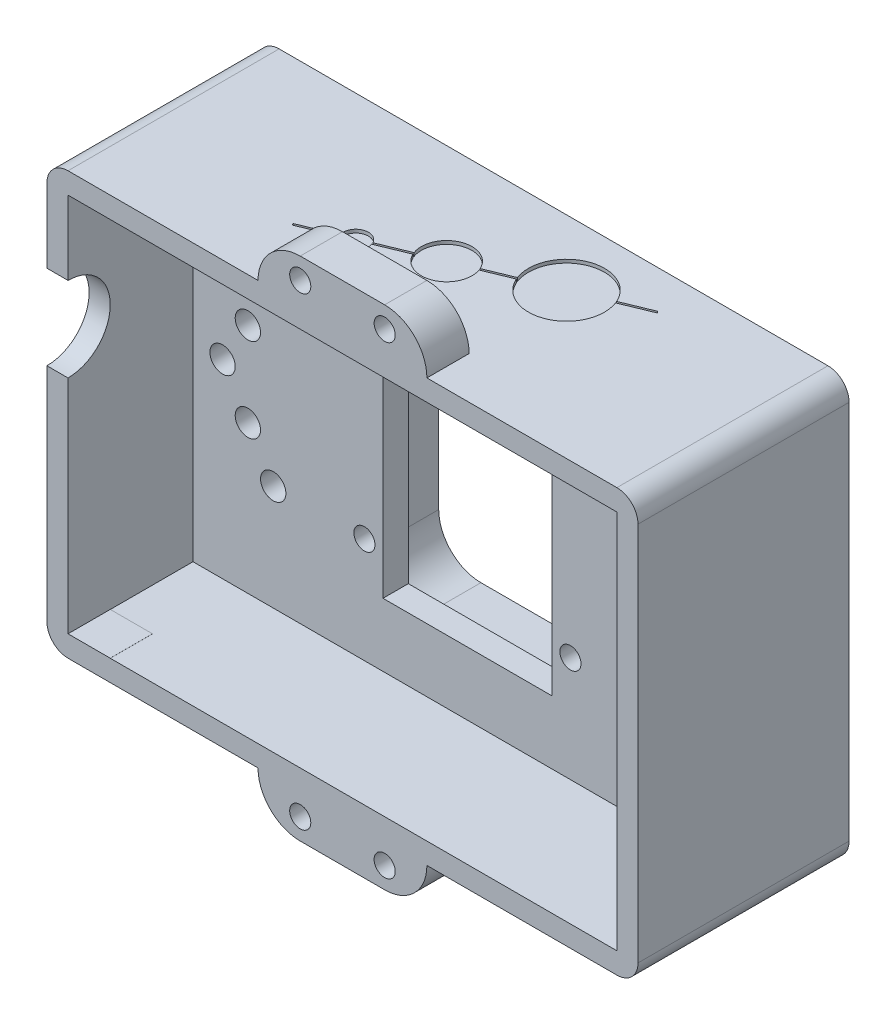
SolidWorks part; units mm, degrees
ref_plane "Front Plane" through (0, 0, 0) normal (0, 0, 1) x (1, 0, 0)
ref_plane "Top Plane" through (0, 0, 0) normal (0, 1, 0) x (1, 0, 0)
ref_plane "Right Plane" through (0, 0, 0) normal (1, 0, 0) x (0, 0, -1)
sketch "Sketch1" plane through (0, 0, 0) normal (0, 0, 1) x (1, 0, 0)
  line L1 (0, 0) -> (76.2, 0)
  line L2 (0, 0) -> (0, -63.5)
  line L3 (0, -63.5) -> (76.2, -63.5)
  line L4 (76.2, 0) -> (76.2, -63.5)
  dimension "D1" = 76.2
  dimension "D2" = 63.5
extrude "Boss-Extrude1" add sketch "Sketch1" along normal blind 31.75
sketch "Sketch2" plane through (0, 0, 31.75) normal (0, 0, 1) x (1, 0, 0)
  line L0 (0, 0) -> (0, -63.5) construction
  line L1 (3.175, -3.175) -> (73.025, -3.175)
  line L2 (3.175, -3.175) -> (3.175, -60.325)
  line L3 (3.175, -60.325) -> (73.025, -60.325)
  line L4 (73.025, -3.175) -> (73.025, -60.325)
  line L5 (76.2, 0) -> (0, 0) construction
  line L6 (76.2, -63.5) -> (76.2, 0) construction
  line L7 (0, -63.5) -> (76.2, -63.5) construction
  dimension "D1" = 3.175
  dimension "D2" = 3.175
  dimension "D3" = 3.175
  dimension "D4" = 3.175
extrude "Cut-Extrude1" cut sketch "Sketch2" against normal blind 28.575
sketch "Sketch3" plane through (0, 0, 0) normal (0, 0, -1) x (-1, 0, 0)
  line L0 (-76.2, 0) -> (0, 0) construction
  line L1 (-47.625, -19.05) -> (-28.575, -19.05)
  line L2 (-47.625, -19.05) -> (-47.625, -44.45)
  line L3 (-47.625, -44.45) -> (-28.575, -44.45)
  line L4 (-28.575, -19.05) -> (-28.575, -44.45)
  line L5 (-76.2, -63.5) -> (-76.2, 0) construction
  point P4 (-38.1, -19.05)
  dimension "D1" = 19.05
  dimension "D2" = 25.4
  dimension "D3" = 19.05
  dimension "D4" = 28.575
extrude "Cut-Extrude2" cut sketch "Sketch3" against normal blind 28.575
sketch "Sketch4" plane through (0, 0, 0) normal (0, 0, -1) x (-1, 0, 0)
  line L0 (-47.625, -19.05) -> (-47.625, -44.45) construction
  line L1 (-28.575, -44.45) -> (-28.575, -19.05) construction
  line L3 (-76.2, 0) -> (0, 0) construction
  line L4 (0, -63.5) -> (-76.2, -63.5) construction
  line L5 (-47.625, -19.05) -> (-47.625, -12.7)
  line L6 (-47.625, -12.7) -> (-28.575, -12.7)
  line L7 (-28.575, -12.7) -> (-28.575, -19.05)
  line L8 (-28.575, -19.05) -> (-47.625, -19.05)
  circle A0 centre (-52.0383, -19.05) radius 1.5875
  circle A1 centre (-24.257, -19.05) radius 1.5875
  circle A2 centre (-52.0382, -44.45) radius 1.5875
  circle A3 centre (-24.257, -44.45) radius 1.5875
  dimension "D1" = 3.175
  dimension "D2" = 27.7812
  dimension "D3" = 4.4132
  dimension "D4" = 4.4132
  dimension "D5" = 27.7812
  dimension "D6" = 4.318
  dimension "D7" = 4.318
  dimension "D8" = 19.05
  dimension "D9" = 19.05
  dimension "D10" = 6.35
extrude "Cut-Extrude3" cut sketch "Sketch4" against normal blind 28.575
sketch "Sketch5" plane through (0, 0, 0) normal (0, 0, -1) x (-1, 0, 0)
  line L0 (-47.625, -44.45) -> (-47.625, -50.8)
  line L1 (-47.625, -50.8) -> (-28.575, -50.8)
  line L2 (-28.575, -50.8) -> (-28.575, -44.45)
  line L3 (-47.625, -44.45) -> (-28.575, -44.45)
  dimension "D1" = 6.35
extrude "Cut-Extrude4" cut sketch "Sketch5" against normal blind 28.575
sketch "Sketch7" plane through (0, 0, 0) normal (0, 1, 0) x (1, 0, 0)
  line L0 (76.2, -31.75) -> (0, -31.75) construction
  line L1 (25.4, -31.75) -> (50.8, -31.75)
  line L2 (25.4, -31.75) -> (25.4, -25.4)
  line L3 (25.4, -25.4) -> (50.8, -25.4)
  line L4 (50.8, -31.75) -> (50.8, -25.4)
  line L5 (0, -31.75) -> (0, 0) construction
  dimension "D1" = 25.4
  dimension "D2" = 6.35
  dimension "D3" = 25.4
extrude "Boss-Extrude2" add sketch "Sketch7" along normal blind 6.35
sketch "Sketch9" plane through (0, 0, 25.4) normal (0, 0, -1) x (-1, 0, 0)
  line L0 (-50.8, 6.35) -> (-50.8, 0) construction
  line L1 (-25.4, 6.35) -> (-25.4, 0) construction
  circle A0 centre (-44.45, 3.175) radius 1.5875
  circle A1 centre (-31.75, 3.175) radius 1.5875
  dimension "D1" = 3.175
  dimension "D2" = 6.35
  dimension "D3" = 6.35
extrude "Cut-Extrude5" cut sketch "Sketch9" against normal blind 6.35
sketch "Sketch10" plane through (0, -63.5, 0) normal (0, -1, 0) x (1, 0, 0)
  line L0 (0, 31.75) -> (76.2, 31.75) construction
  line L1 (25.4, 31.75) -> (50.8, 31.75)
  line L2 (25.4, 31.75) -> (25.4, 25.4)
  line L3 (25.4, 25.4) -> (50.8, 25.4)
  line L4 (50.8, 31.75) -> (50.8, 25.4)
  line L5 (76.2, 31.75) -> (76.2, 0) construction
  dimension "D1" = 25.4
  dimension "D2" = 6.35
  dimension "D3" = 25.4
extrude "Boss-Extrude3" add sketch "Sketch10" along normal blind 6.35
sketch "Sketch11" plane through (0, 0, 25.4) normal (0, 0, -1) x (-1, 0, 0)
  line L0 (-50.8, -69.85) -> (-50.8, -63.5) construction
  line L1 (-25.4, -69.85) -> (-25.4, -63.5) construction
  circle A0 centre (-44.45, -66.675) radius 1.5875
  circle A1 centre (-31.75, -66.675) radius 1.5875
  dimension "D1" = 6.35
  dimension "D2" = 6.35
extrude "Cut-Extrude6" cut sketch "Sketch11" against normal blind 6.35
sketch "Sketch12" plane through (76.2, 0, 0) normal (1, 0, 0) x (0, 0, -1)
  line L1 (-31.75, -63.5) -> (-31.75, 0) construction
  line L2 (-31.75, -63.5) -> (0, -63.5) construction
  circle A1 centre (-31.75, -28.575) radius 6.35
  dimension "D1" = 34.925
  dimension "D2" = 12.7
extrude "Cut-Extrude8" cut sketch "Sketch12" against normal blind 6.35
sketch "Sketch13" plane through (76.2, 0, 0) normal (1, 0, 0) x (0, 0, -1)
  line L1 (-31.75, -22.225) -> (-24.5719, -22.225)
  line L2 (-31.75, -22.225) -> (-31.75, -35.8201)
  line L3 (-31.75, -35.8201) -> (-24.5719, -35.8201)
  line L4 (-24.5719, -22.225) -> (-24.5719, -35.8201)
extrude "Boss-Extrude4" add sketch "Sketch13" against normal blind 3.175
sketch "Sketch14" plane through (76.2, 0, 0) normal (1, 0, 0) x (0, 0, -1)
  line L0 (-31.75, -63.5) -> (-31.75, 0) construction
  line L1 (-25.4, -63.5) -> (-31.75, -63.5) construction
  circle A0 centre (-31.75, -25.4) radius 6.35
  dimension "D1" = 12.7
  dimension "D2" = 38.1
extrude "Cut-Extrude9" cut sketch "Sketch14" against normal blind 3.175
sketch "Sketch15" plane through (0, 0, 0) normal (0, 0, -1) x (-1, 0, 0)
  circle A0 centre (-52.0383, -19.05) radius 1.5875
  circle A1 centre (-24.257, -19.05) radius 1.5875
  circle A2 centre (-24.257, -44.45) radius 1.5875
  circle A3 centre (-52.0382, -44.45) radius 1.5875
sketch "Sketch16" plane through (0, 0, 0) normal (0, 0, -1) x (-1, 0, 0)
  line L0 (-52.0383, -19.05) -> (-52.0383, 0)
  line L1 (-76.2, 0) -> (0, 0) construction
  line L2 (-24.257, -19.05) -> (-24.257, 0)
  line L3 (-52.0382, -44.45) -> (-52.0382, -63.5)
  line L4 (0, -63.5) -> (-76.2, -63.5) construction
  line L5 (-24.257, -44.45) -> (-24.257, -63.5)
  circle A0 centre (-53.6258, -19.05) radius 1.5875
  circle A1 centre (-52.0383, -19.05) radius 1.5875 construction
  circle A2 centre (-53.6257, -44.45) radius 1.5875
  circle A3 centre (-52.0382, -44.45) radius 1.5875 construction
  circle A4 centre (-22.6695, -19.05) radius 1.5875
  circle A5 centre (-24.257, -19.05) radius 1.5875 construction
  circle A6 centre (-22.6695, -44.45) radius 1.5875
  circle A7 centre (-24.257, -44.45) radius 1.5875 construction
  circle M2 centre (-52.0382, -44.45) radius 1.5875
  circle M3 centre (-24.257, -19.05) radius 1.5875
  circle M4 centre (-52.0383, -19.05) radius 1.5875
extrude "Boss-Extrude8" add sketch "Sketch15" against normal blind 3.175
extrude "Cut-Extrude11" cut sketch "Sketch16" against normal blind 8.509 contours A0 M4 | A0 M4 | A4 M3 | A4 M3 | A2 M2 | A2 M2 | A6
sketch "Sketch18" plane through (0, 0, 0) normal (0, 0, -1) x (-1, 0, 0)
  line L0 (-50.1096, -12.7) -> (-47.625, -12.7)
  line L1 (-47.625, -12.7) -> (-26.0904, -12.7)
  line L2 (-47.625, -10.2154) -> (-28.575, -10.2154)
  arc A0 (-47.625, -10.2154) -> (-50.1096, -12.7) centre (-47.625, -12.7) ccw
  arc A1 (-28.575, -10.2154) -> (-26.0904, -12.7) centre (-28.575, -12.7) cw
extrude "Cut-Extrude12" cut sketch "Sketch18" against normal blind 8.509
sketch "Sketch26" plane through (0, 0, 0) normal (0, 0, -1) x (-1, 0, 0)
  line L1 (-76.2, 0) -> (0, 0) construction
  line L2 (0, -63.5) -> (-76.2, -63.5) construction
  line L3 (0, 0) -> (0, -63.5) construction
  line L4 (-76.2, -63.5) -> (-76.2, 0) construction
  circle A0 centre (-68.58, -31.75) radius 2.921
  circle A1 centre (-64.77, -25.4) radius 2.921
  circle A2 centre (-60.96, -19.05) radius 2.921
  circle A3 centre (-64.77, -38.1) radius 2.921
  circle A4 centre (-60.96, -44.45) radius 2.921
  circle A5 centre (-7.62, -31.75) radius 2.921
  circle A6 centre (-11.43, -25.4) radius 2.921
  circle A7 centre (-15.24, -19.05) radius 2.921
  circle A8 centre (-11.43, -38.1) radius 2.921
  circle A9 centre (-15.24, -44.45) radius 2.921
  dimension "D3" = 7.62
  dimension "D4" = 11.43
  dimension "D5" = 15.24
  dimension "D6" = 11.43
  dimension "D7" = 15.24
  dimension "D12" = 7.62
  dimension "D13" = 11.43
  dimension "D14" = 11.43
  dimension "D15" = 15.24
  dimension "D16" = 15.24
  dimension "D17" = 31.75
  dimension "D18" = 25.4
  dimension "D19" = 19.05
  dimension "D20" = 25.4
  dimension "D21" = 19.05
extrude "Cut-Extrude24" cut sketch "Sketch26" against normal blind 72.898
sketch "Sketch32" plane through (0, 0, 3.175) normal (0, 0, 1) x (1, 0, 0)
  line L1 (3.175, -3.175) -> (73.025, -3.175)
  line L2 (3.175, -3.175) -> (3.175, -60.325)
  line L3 (3.175, -60.325) -> (73.025, -60.325)
  line L4 (73.025, -3.175) -> (73.025, -60.325)
  circle A0 centre (15.24, -19.05) radius 2.921
  circle A1 centre (11.43, -25.4) radius 2.921
  circle A2 centre (7.62, -31.75) radius 2.921
  circle A3 centre (11.43, -38.1) radius 2.921
  circle A4 centre (15.24, -44.45) radius 2.921
  circle A5 centre (60.96, -44.45) radius 2.921
  circle A6 centre (64.77, -38.1) radius 2.921
  circle A7 centre (68.58, -31.75) radius 2.921
  circle A8 centre (64.77, -25.4) radius 2.921
  circle A9 centre (60.96, -19.05) radius 2.921
extrude "Boss-Extrude10" add sketch "Sketch32" along normal blind 5.715
sketch "Sketch36" plane through (0, 0, 0) normal (0, 0, -1) x (-1, 0, 0)
  line L1 (-55.2133, -17.4625) -> (-21.082, -17.4625)
  line L2 (-55.2133, -17.4625) -> (-55.2133, -46.0375)
  line L3 (-55.2133, -46.0375) -> (-21.082, -46.0375)
  line L4 (-21.082, -17.4625) -> (-21.082, -46.0375)
extrude "Cut-Extrude27" cut sketch "Sketch36" against normal blind 38.227 contours L2 L1 L4 L3
sketch "Sketch38" plane through (0, 0, 0) normal (0, 0, -1) x (-1, 0, 0)
  line L0 (-55.2133, -46.0375) -> (-21.082, -46.0375)
  spline S0 degree 3 poles (-55.2133, -46.0375) (-46.3247, -54.6455) (-29.9359, -54.7487) (-21.082, -46.0375) knots 0 0 0 0 1 1 1 1
extrude "Cut-Extrude29" cut sketch "Sketch38" against normal blind 38.227
sketch "Sketch39" plane through (0, 0, 8.89) normal (0, 0, 1) x (1, 0, 0)
  line L0 (3.175, -60.325) -> (73.025, -60.325) construction
  line L1 (3.175, -3.175) -> (21.082, -3.175)
  line L2 (3.175, -3.175) -> (3.175, -60.325)
  line L3 (3.175, -60.325) -> (21.082, -60.325)
  line L4 (21.082, -3.175) -> (21.082, -60.325)
  line L6 (73.025, -3.175) -> (55.2132, -3.175)
  line L7 (73.025, -3.175) -> (73.025, -60.325)
  line L8 (73.025, -60.325) -> (55.2132, -60.325)
  line L9 (55.2132, -3.175) -> (55.2132, -60.325)
  circle A0 centre (15.24, -19.05) radius 1.905
  circle A1 centre (11.43, -25.4) radius 1.905
  circle A2 centre (7.62, -31.75) radius 1.905
  circle A3 centre (11.43, -38.1) radius 1.905
  circle A4 centre (15.24, -44.45) radius 1.905
  circle A5 centre (60.96, -44.45) radius 1.905
  circle A6 centre (64.77, -38.1) radius 1.905
  circle A7 centre (68.58, -31.75) radius 1.905
  circle A8 centre (64.77, -25.4) radius 1.905
  circle A9 centre (60.96, -19.05) radius 1.905
  dimension "D1" = 3.81
extrude "Boss-Extrude11" add sketch "Sketch39" along normal blind 2.54
sketch "Sketch44" plane through (0, 0, 0) normal (0, 0, -1) x (-1, 0, 0)
  line L0 (-28.575, -12.7) -> (-28.575, -17.4625) construction
  line L1 (-28.575, -17.4625) -> (-47.625, -17.4625) construction
  line L2 (-47.625, -9.8743) -> (-28.575, -9.9695)
  line L3 (-21.082, -17.4625) -> (-55.2133, -17.4625)
  arc A0 (-55.2133, -17.4625) -> (-47.625, -9.8743) centre (-47.625, -17.4625) cw
  arc A1 (-21.082, -17.4625) -> (-28.575, -9.9695) centre (-28.575, -17.4625) ccw
extrude "Cut-Extrude34" cut sketch "Sketch44" against normal blind 11.176
sketch "Sketch47" plane through (0, 0, 0) normal (0, 0, -1) x (-1, 0, 0)
  line L0 (-76.2, 0) -> (0, 0) construction
  line L1 (-55.372, -9.144) -> (-20.828, -9.144)
  line L2 (-55.372, -9.144) -> (-55.372, -54.356)
  line L3 (-55.372, -54.356) -> (-20.828, -54.356)
  line L4 (-20.828, -9.144) -> (-20.828, -54.356)
  line L5 (-76.2, -63.5) -> (-76.2, 0) construction
  line L6 (-44.0174, -9.144) -> (-55.372, -9.144)
  line L7 (-55.372, -44.45) -> (-55.372, -54.356)
  line L8 (-32.3914, -54.356) -> (-20.828, -54.356)
  line L9 (-32.3914, -9.144) -> (-20.828, -9.144)
  spline S0 degree 2 poles (-55.372, -19.05) (-51.6624, -8.9987) (-44.0174, -9.144) knots 0 0 0 1 1 1
  spline S1 degree 2 poles (-20.828, -19.05) (-24.615, -8.9285) (-32.3914, -9.144) knots 0 0 0 1 1 1
  spline S2 degree 2 poles (-55.372, -44.45) (-51.6624, -54.5013) (-44.0174, -54.356) knots 0 0 0 1 1 1
  spline S3 degree 2 poles (-20.828, -44.45) (-24.615, -54.5715) (-32.3914, -54.356) knots 0 0 0 1 1 1
  point P4 (-55.372, -31.75)
  point P7 (-38.1, -9.144)
  dimension "D1" = 34.544
  dimension "D2" = 45.212
  dimension "D3" = 31.75
  dimension "D4" = 38.1
extrude "Cut-Extrude36" cut sketch "Sketch47" against normal blind 11.43 contours L2 L1 L4 L3
sketch "Sketch51" plane through (76.2, 0, 0) normal (1, 0, 0) x (0, 0, -1)
  line L1 (0, 0) -> (-31.75, 0)
  line L2 (0, 0) -> (0, -63.5)
  line L3 (0, -63.5) -> (-31.75, -63.5)
  line L4 (-31.75, 0) -> (-31.75, -63.5)
extrude "Boss-Extrude16" add sketch "Sketch51" along normal blind 6.35
sketch "Sketch52" plane through (0, 0, 0) normal (-1, 0, 0) x (0, 0, 1)
  line L1 (0, 0) -> (31.75, 0)
  line L2 (0, 0) -> (0, -63.5)
  line L3 (0, -63.5) -> (31.75, -63.5)
  line L4 (31.75, 0) -> (31.75, -63.5)
extrude "Boss-Extrude17" add sketch "Sketch52" along normal blind 6.35
sketch "Sketch53" plane through (76.2, 0, 0) normal (-1, 0, 0) x (0, 0, 1)
  line L0 (31.75, -19.05) -> (31.75, -31.75) construction
  circle A0 centre (31.75, -25.4) radius 6.35
extrude "Cut-Extrude37" cut sketch "Sketch53" against normal blind 6.35
sketch "Sketch54" plane through (0, 0, 31.75) normal (0, 0, 1) x (1, 0, 0)
  line L1 (3.175, -3.175) -> (-3.175, -3.175)
  line L2 (3.175, -3.175) -> (3.175, -60.1885)
  line L3 (3.175, -60.1885) -> (-3.175, -60.1885)
  line L4 (-3.175, -3.175) -> (-3.175, -60.1885)
  line L5 (73.025, -3.175) -> (79.375, -3.175)
  line L6 (73.025, -3.175) -> (73.025, -60.325)
  line L7 (73.025, -60.325) -> (79.375, -60.325)
  line L8 (79.375, -3.175) -> (79.375, -60.325)
  dimension "D1" = 6.35
  dimension "D2" = 6.35
extrude "Cut-Extrude38" cut sketch "Sketch54" against normal blind 21.59
sketch "Sketch57" plane through (0, 0, 10.16) normal (0, 0, 1) x (1, 0, 0)
  line L1 (-3.175, -3.175) -> (3.175, -3.175)
  line L2 (-3.175, -3.175) -> (-3.175, -60.325)
  line L3 (-3.175, -60.325) -> (3.175, -60.325)
  line L4 (3.175, -3.175) -> (3.175, -60.325)
  line L5 (73.025, -60.325) -> (79.375, -60.325)
  line L6 (73.025, -60.325) -> (73.025, -3.175)
  line L7 (73.025, -3.175) -> (79.375, -3.175)
  line L8 (79.375, -60.325) -> (79.375, -3.175)
extrude "Boss-Extrude20" add sketch "Sketch57" along normal blind 1.27
sketch "Sketch59" plane through (0, 0, 0) normal (0, 0, -1) x (-1, 0, 0)
  line L1 (-56.5485, -13.4059) -> (-73.3958, -13.4059)
  line L2 (-56.5485, -13.4059) -> (-56.5485, -49.4675)
  line L3 (-56.5485, -49.4675) -> (-73.3958, -49.4675)
  line L4 (-73.3958, -13.4059) -> (-73.3958, -49.4675)
  line L5 (-19.1642, -12.2921) -> (-2.4561, -12.2921)
  line L6 (-19.1642, -12.2921) -> (-19.1642, -48.9106)
  line L7 (-19.1642, -48.9106) -> (-2.4561, -48.9106)
  line L8 (-2.4561, -12.2921) -> (-2.4561, -48.9106)
extrude "Boss-Extrude21" add sketch "Sketch59" against normal blind 11.43
sketch "Sketch61" plane through (0, 0, 0) normal (0, 0, -1) x (-1, 0, 0)
  line L0 (-82.55, -63.5) -> (-82.55, 0) construction
  line L1 (-82.55, 0) -> (6.35, 0) construction
  line L2 (6.35, -63.5) -> (-82.55, -63.5) construction
  line L3 (6.35, 0) -> (6.35, -63.5) construction
  circle A0 centre (-74.93, -31.75) radius 2.921
  circle A1 centre (-71.12, -25.4) radius 2.921
  circle A2 centre (73.7439, -27.6774) radius 2.921
  circle A3 centre (-67.31, -19.05) radius 2.921
  circle A4 centre (-71.12, -38.1) radius 2.921
  circle A5 centre (-67.31, -44.45) radius 2.921
  circle A6 centre (-1.27, -31.75) radius 2.921
  circle A7 centre (-5.08, -25.4) radius 2.921
  circle A8 centre (-8.89, -19.05) radius 2.921
  circle A9 centre (-5.08, -38.1) radius 2.921
  circle A10 centre (-8.89, -44.45) radius 2.921
  dimension "D1" = 7.62
  dimension "D2" = 11.43
  dimension "D3" = 11.43
  dimension "D4" = 15.24
  dimension "D5" = 15.24
  dimension "D6" = 31.75
  dimension "D7" = 25.4
  dimension "D8" = 25.4
  dimension "D9" = 19.05
  dimension "D10" = 19.05
  dimension "D11" = 7.62
  dimension "D12" = 31.75
  dimension "D13" = 11.43
  dimension "D14" = 25.4
  dimension "D15" = 19.05
  dimension "D16" = 15.24
  dimension "D17" = 11.43
  dimension "D18" = 25.4
  dimension "D19" = 15.24
  dimension "D20" = 19.05
extrude "Cut-Extrude39" cut sketch "Sketch61" against normal blind 8.89
sketch "Sketch62" plane through (0, 0, 8.89) normal (0, 0, -1) x (-1, 0, 0)
  circle A0 centre (-67.31, -19.05) radius 1.905
  circle A1 centre (-71.12, -25.4) radius 1.905
  circle A2 centre (-74.93, -31.75) radius 1.905
  circle A3 centre (-71.12, -38.1) radius 1.905
  circle A4 centre (-67.31, -44.45) radius 1.905
  circle A5 centre (-8.89, -44.45) radius 1.905
  circle A6 centre (-5.08, -38.1) radius 1.905
  circle A7 centre (-1.27, -31.75) radius 1.905
  circle A8 centre (-5.08, -25.4) radius 1.905
  circle A9 centre (-8.89, -19.05) radius 1.905
  dimension "D1" = 3.81
extrude "Cut-Extrude40" cut sketch "Sketch62" against normal blind 2.54
sketch "Sketch63" plane through (-3.175, 0, 0) normal (1, 0, 0) x (0, 0, -1)
  line L6 (-11.43, -3.175) -> (-31.75, -3.175) construction
  line L7 (-20.32, -3.175) -> (-21.59, -3.175)
  line L8 (-20.32, -3.175) -> (-20.32, -60.1885)
  line L9 (-20.32, -60.1885) -> (-21.59, -60.1885)
  line L10 (-21.59, -3.175) -> (-21.59, -60.1885)
  line L11 (-11.43, -60.1885) -> (-31.75, -60.1885) construction
  line L12 (-11.43, -3.175) -> (-11.43, -60.1885) construction
  line L14 (-21.59, -3.175) -> (-25.4, -3.175)
  line L15 (-21.59, -3.175) -> (-21.59, -60.1885)
  line L16 (-21.59, -60.1885) -> (-25.4, -60.1885)
  line L17 (-25.4, -3.175) -> (-25.4, -60.1885)
  dimension "D1" = 8.89
  dimension "D2" = 1.27
  dimension "D3" = 3.81
sketch "Sketch64" plane through (0, -60.1885, 0) normal (0, 1, 0) x (1, 0, 0)
  line L1 (-3.175, -11.43) -> (3.175, -11.43)
  line L2 (-3.175, -11.43) -> (-3.175, -31.75)
  line L3 (-3.175, -31.75) -> (3.175, -31.75)
  line L4 (3.175, -11.43) -> (3.175, -31.75)
extrude "Cut-Extrude42" cut sketch "Sketch64" against normal blind 0.127
extrude "Boss-Extrude22" add sketch "Sketch63" along normal blind 83.439 contours L8 L7 L10 L9 | L15 L14 L17 L16
sketch "Sketch65" plane through (0, 0, 0) normal (0, 0, -1) x (-1, 0, 0)
  line L0 (-82.55, 0) -> (6.35, 0) construction
  line L1 (6.35, 0) -> (6.35, -63.5) construction
  line L2 (-82.55, -63.5) -> (-82.55, 0) construction
  circle A0 centre (-53.594, -19.05) radius 1.5875
  circle A1 centre (-22.606, -19.05) radius 1.5875
  circle A2 centre (-22.606, -44.45) radius 1.5875
  circle A3 centre (-53.594, -44.45) radius 1.5875
  dimension "D1" = 3.175
  dimension "D2" = 25.4
  dimension "D3" = 25.4
  dimension "D4" = 19.05
  dimension "D5" = 19.05
  dimension "D6" = 28.956
  dimension "D7" = 28.956
  dimension "D8" = 28.956
  dimension "D9" = 28.956
extrude "Cut-Extrude43" cut sketch "Sketch65" against normal blind 83.439
sketch "Sketch66" plane through (0, 0, 20.32) normal (0, 0, -1) x (-1, 0, 0)
  line L0 (-82.55, -63.5) -> (-82.55, 0) construction
  line L1 (-50.8, -12.7) -> (-25.4, -12.7)
  line L2 (-50.8, -12.7) -> (-50.8, -50.8)
  line L3 (-50.8, -50.8) -> (-25.4, -50.8)
  line L4 (-25.4, -12.7) -> (-25.4, -50.8)
  line L5 (-82.55, 0) -> (6.35, 0) construction
  point P4 (-50.8, -31.75)
  point P6 (-38.1, -12.7)
  dimension "D3" = 44.45
  dimension "D1" = 25.4
  dimension "D2" = 38.1
  dimension "D4" = 31.75
extrude "Cut-Extrude44" cut sketch "Sketch66" against normal blind 83.439
sketch "Sketch67" plane through (0, 0, 0) normal (0, 0, -1) x (-1, 0, 0)
  line L0 (-55.372, -9.144) -> (-55.372, -54.356) construction
  line L1 (-55.372, -9.144) -> (-20.828, -9.144) construction
  line L2 (-20.828, -9.144) -> (-20.828, -54.356) construction
  line L3 (-55.372, -54.356) -> (-20.828, -54.356) construction
  line L4 (-53.6737, -9.144) -> (-55.372, -9.144)
  line L5 (-55.372, -9.144) -> (-55.372, -12.7)
  line L6 (-55.372, -50.8) -> (-55.372, -54.356)
  line L7 (-55.372, -54.356) -> (-53.6737, -54.356)
  line L8 (-22.5263, -54.356) -> (-20.828, -54.356)
  line L9 (-20.828, -54.356) -> (-20.828, -50.8)
  line L10 (-20.828, -12.7) -> (-20.828, -9.144)
  line L11 (-20.828, -9.144) -> (-22.5263, -9.144)
  arc A0 (-55.372, -12.7) -> (-53.6737, -9.144) centre (-50.8, -12.7) cw
  arc A1 (-20.828, -12.7) -> (-22.5263, -9.144) centre (-25.4, -12.7) ccw
  arc A2 (-20.828, -50.8) -> (-22.5263, -54.356) centre (-25.4, -50.8) cw
  arc A3 (-55.372, -50.8) -> (-53.6737, -54.356) centre (-50.8, -50.8) ccw
extrude "Boss-Extrude23" add sketch "Sketch67" against normal blind 11.43
sketch "Sketch68" plane through (0, 0, 20.32) normal (0, 0, -1) x (-1, 0, 0)
  line L0 (-67.31, -17.145) -> (-65.405, -19.05)
  line L1 (-65.405, -19.05) -> (-73.025, -31.75)
  line L2 (-73.025, -31.75) -> (-65.405, -44.45)
  line L3 (-65.405, -44.45) -> (-67.31, -46.355)
  line L4 (-67.31, -46.355) -> (-76.835, -31.75)
  line L5 (-76.835, -31.75) -> (-67.31, -17.145)
  line L6 (-10.795, -19.05) -> (-8.89, -17.145)
  line L7 (-8.89, -17.145) -> (0.635, -31.75)
  line L8 (0.635, -31.75) -> (-8.89, -46.355)
  line L9 (-8.89, -46.355) -> (-10.795, -44.45)
  line L10 (-10.795, -44.45) -> (-3.175, -31.75)
  line L11 (-3.175, -31.75) -> (-10.795, -19.05)
  circle A0 centre (-67.31, -19.05) radius 1.905 construction
  circle A1 centre (-74.93, -31.75) radius 1.905 construction
  circle A2 centre (-67.31, -44.45) radius 1.905 construction
  circle A3 centre (-8.89, -19.05) radius 1.905 construction
  circle A4 centre (-1.27, -31.75) radius 1.905 construction
  circle A5 centre (-8.89, -44.45) radius 1.905 construction
extrude "Cut-Extrude45" cut sketch "Sketch68" against normal blind 11.43
sketch "Sketch71" plane through (0, 0, 31.75) normal (0, 0, 1) x (1, 0, 0)
  line L0 (25.4, 0) -> (-6.35, 0) construction
  line L1 (-6.35, -63.5) -> (-6.35, 0) construction
  line L2 (82.55, 0) -> (50.8, 0) construction
  line L3 (82.55, 0) -> (82.55, -19.05) construction
  line L4 (82.55, -31.75) -> (82.55, -63.5) construction
  line L5 (50.8, -63.5) -> (82.55, -63.5) construction
  line L6 (-3.175, 0) -> (-6.35, 0)
  line L7 (-6.35, 0) -> (-6.35, -3.175)
  line L8 (-6.35, -60.3155) -> (-6.35, -63.5)
  line L9 (-6.35, -63.5) -> (-3.175, -63.4905)
  line L10 (82.55, -60.325) -> (82.55, -63.5)
  line L11 (82.55, -63.5) -> (79.375, -63.5)
  line L12 (79.375, 0) -> (82.55, 0)
  line L13 (82.55, 0) -> (82.55, -3.175)
  arc A0 (-3.175, 0) -> (-6.35, -3.175) centre (-3.175, -3.175) ccw
  arc A1 (79.375, 0) -> (82.55, -3.175) centre (79.375, -3.175) cw
  arc A2 (82.55, -60.325) -> (79.375, -63.5) centre (79.375, -60.325) cw
  arc A3 (-6.35, -60.3155) -> (-3.175, -63.4905) centre (-3.175, -60.3155) ccw
extrude "Cut-Extrude47" cut sketch "Sketch71" against normal blind 63.5
sketch "Sketch72" plane through (-3.175, 0, 0) normal (1, 0, 0) x (0, 0, -1)
  circle A0 centre (-31.75, -25.4) radius 6.35
extrude "Cut-Extrude48" cut sketch "Sketch72" against normal blind 63.5
sketch "Sketch73" plane through (82.55, 0, 0) normal (1, 0, 0) x (0, 0, -1)
  line L0 (-31.75, -3.175) -> (-31.75, -19.05) construction
  line L1 (-31.75, -19.05) -> (-23.8556, -19.05)
  line L2 (-31.75, -19.05) -> (-31.75, -31.75)
  line L3 (-31.75, -31.75) -> (-23.8556, -31.75)
  line L4 (-23.8556, -19.05) -> (-23.8556, -31.75)
  arc A0 (-31.75, -31.75) -> (-31.75, -19.05) centre (-31.75, -25.4) ccw construction
extrude "Boss-Extrude24" add sketch "Sketch73" against normal blind 3.175
sketch "Sketch74" plane through (0, 0, 25.4) normal (0, 0, -1) x (-1, 0, 0)
  line L0 (-50.8, 0) -> (-25.4, 0) construction
  line L5 (-44.45, 6.35) -> (-50.8, 6.35)
  line L10 (-50.8, 6.35) -> (-50.8, 0)
  line L11 (-31.75, 6.35) -> (-25.4, 6.35)
  line L12 (-25.4, 6.35) -> (-25.4, 0)
  arc A0 (-44.45, 6.35) -> (-50.8, 0) centre (-44.45, 0) ccw
  arc A1 (-31.75, 6.35) -> (-25.4, 0) centre (-31.75, 0) cw
extrude "Cut-Extrude49" cut sketch "Sketch74" against normal blind 9.779
sketch "Sketch75" plane through (0, 0, 25.4) normal (0, 0, -1) x (-1, 0, 0)
  line L0 (6.35, -63.5) -> (-79.375, -63.5) construction
  line L5 (-25.4, -63.5) -> (-50.8, -63.5) construction
  line L10 (-50.8, -63.5) -> (-50.8, -69.85)
  line L11 (-50.8, -69.85) -> (-44.45, -69.85)
  line L12 (-31.75, -69.85) -> (-25.4, -69.85)
  line L13 (-25.4, -69.85) -> (-25.4, -63.5)
  arc A0 (-50.8, -63.5) -> (-44.45, -69.85) centre (-44.45, -63.5) ccw
  arc A1 (-25.4, -63.5) -> (-31.75, -69.85) centre (-31.75, -63.5) cw
  dimension "D1" = 6.35
  dimension "D2" = 6.35
extrude "Cut-Extrude50" cut sketch "Sketch75" against normal blind 9.779
sketch "Sketch76" plane through (0, 0, 20.32) normal (0, 0, -1) x (-1, 0, 0)
  line L0 (-67.31, -16.129) -> (-64.389, -19.05)
  line L1 (-64.389, -19.05) -> (-72.009, -31.75)
  line L2 (-72.009, -31.75) -> (-64.389, -44.45)
  line L3 (-64.389, -44.45) -> (-67.31, -47.371)
  line L4 (-67.31, -47.371) -> (-77.851, -31.75)
  line L5 (-77.851, -31.75) -> (-67.31, -16.129)
  line L6 (-11.811, -19.05) -> (-8.89, -16.129)
  line L7 (-8.89, -16.129) -> (1.651, -31.75)
  line L8 (1.651, -31.75) -> (-7.5154, -47.0274)
  line L9 (-7.5154, -47.0274) -> (-11.811, -44.45)
  line L10 (-11.811, -44.45) -> (-4.191, -31.75)
  line L11 (-4.191, -31.75) -> (-11.811, -19.05)
  circle A0 centre (-67.31, -19.05) radius 2.921 construction
  circle A1 centre (-67.31, -19.05) radius 2.921 construction
  circle A2 centre (-74.93, -31.75) radius 2.921 construction
  circle A3 centre (-74.93, -31.75) radius 2.921 construction
  circle A4 centre (-67.31, -44.45) radius 2.921 construction
  circle A5 centre (-67.31, -44.45) radius 2.921 construction
  circle A6 centre (-8.89, -19.05) radius 2.921 construction
  circle A7 centre (-8.89, -19.05) radius 2.921 construction
  circle A8 centre (-1.27, -31.75) radius 2.921 construction
  circle A9 centre (-1.27, -31.75) radius 2.921 construction
  circle A10 centre (-8.89, -44.45) radius 2.921 construction
  circle A11 centre (-8.89, -44.45) radius 2.921 construction
extrude "Cut-Extrude51" cut sketch "Sketch76" against normal blind 9.779
sketch "Sketch81" plane through (0, 0, 31.75) normal (0, 0, 1) x (1, 0, 0)
  line L1 (-3.175, -63.4905) -> (-6.4183, -63.4905)
  line L2 (-3.175, -63.4905) -> (-3.175, -63.525)
  line L3 (-3.175, -63.525) -> (-6.4183, -63.525)
  line L4 (-6.4183, -63.4905) -> (-6.4183, -63.525)
extrude "Cut-Extrude52" cut sketch "Sketch81" against normal blind 36.703
sketch "Sketch85" plane through (0, 0, 0) normal (0, 0, -1) x (-1, 0, 0)
  circle A0 centre (-67.31, -19.05) radius 2.921
  circle A1 centre (-71.12, -25.4) radius 2.921
  circle A2 centre (-74.93, -31.75) radius 2.921
  circle A3 centre (-71.12, -38.1) radius 2.921
  circle A4 centre (-67.31, -44.45) radius 2.921
  circle A5 centre (-8.89, -44.45) radius 2.921
  circle A6 centre (-5.08, -38.1) radius 2.921
  circle A7 centre (-1.27, -31.75) radius 2.921
  circle A8 centre (-5.08, -25.4) radius 2.921
  circle A9 centre (-8.89, -19.05) radius 2.921
extrude "Cut-Extrude53" cut sketch "Sketch85" against normal blind 11.43
sketch "Sketch86" plane through (0, 0, 11.43) normal (0, 0, 1) x (1, 0, 0)
  line L1 (-3.175, -3.175) -> (79.375, -3.175)
  line L2 (-3.175, -3.175) -> (-3.175, -60.325)
  line L3 (-3.175, -60.325) -> (79.375, -60.325)
  line L4 (79.375, -3.175) -> (79.375, -60.325)
  circle A0 centre (5.08, -25.4) radius 1.905
  circle A1 centre (8.89, -19.05) radius 1.905
  circle A2 centre (1.27, -31.75) radius 1.905
  circle A3 centre (5.08, -38.1) radius 1.905
  circle A4 centre (8.89, -44.45) radius 1.905
  circle A5 centre (67.31, -19.05) radius 1.905
  circle A6 centre (71.12, -25.4) radius 1.905
  circle A7 centre (74.93, -31.75) radius 1.905
  circle A8 centre (71.12, -38.1) radius 1.905
  circle A9 centre (67.31, -44.45) radius 1.905
  dimension "D1" = 3.81
extrude "Boss-Extrude28" add sketch "Sketch86" along normal blind 2.54
sketch "Sketch87" plane through (0, 0, 25.4) normal (0, 0, 1) x (1, 0, 0)
  line L0 (25.4, -12.7) -> (50.8, -12.7) construction
  line L1 (25.4698, -12.7) -> (50.8, -12.7)
  line L2 (25.4698, -12.7) -> (25.4698, -50.8)
  line L3 (25.4698, -50.8) -> (50.8, -50.8)
  line L4 (50.8, -12.7) -> (50.8, -50.8)
  circle A0 centre (22.606, -19.05) radius 1.5875
  circle A1 centre (53.594, -19.05) radius 1.5875
  circle A2 centre (53.594, -44.45) radius 1.5875
  circle A3 centre (22.606, -44.45) radius 1.5875
extrude "Cut-Extrude54" cut sketch "Sketch87" against normal blind 38.862
sketch "Sketch88" plane through (0, 0, 11.43) normal (0, 0, -1) x (-1, 0, 0)
  line L1 (-55.372, -12.7) -> (-20.828, -12.7)
  line L2 (-55.372, -12.7) -> (-55.372, -50.8)
  line L3 (-55.372, -50.8) -> (-20.828, -50.8)
  line L4 (-20.828, -12.7) -> (-20.828, -50.8)
  line L5 (-53.6737, -9.144) -> (-22.5263, -9.144)
  line L6 (-53.6737, -9.144) -> (-53.6737, -12.7)
  line L7 (-53.6737, -12.7) -> (-22.5263, -12.7)
  line L8 (-22.5263, -9.144) -> (-22.5263, -12.7)
  line L9 (-53.6737, -54.356) -> (-22.5263, -54.356)
  line L10 (-53.6737, -54.356) -> (-53.6737, -50.8)
  line L11 (-53.6737, -50.8) -> (-22.5263, -50.8)
  line L12 (-22.5263, -54.356) -> (-22.5263, -50.8)
  arc A0 (-55.372, -12.7) -> (-53.6737, -9.144) centre (-50.8, -12.7) cw
  arc A1 (-20.828, -12.7) -> (-22.4774, -9.1515) centre (-25.4698, -12.7) ccw
  arc A2 (-20.828, -50.8) -> (-22.5529, -54.4108) centre (-25.4698, -50.8) cw
  arc A3 (-55.372, -50.8) -> (-53.6737, -54.356) centre (-50.8, -50.8) ccw
  arc A4 (-55.372, -50.8) -> (-53.6737, -54.356) centre (-50.8, -50.8) ccw construction
extrude "Cut-Extrude55" cut sketch "Sketch88" against normal blind 2.54 contours L6 L5 L8 L7 | L2 L1 L4 L3 | L10 L9 L12 L11
sketch "Sketch89" plane through (0, 0, 11.43) normal (0, 0, -1) x (-1, 0, 0)
  line L0 (-53.6737, -9.144) -> (-53.6737, -12.7) construction
  line L1 (-53.6737, -9.144) -> (-22.5263, -9.144)
  line L2 (-20.828, -50.8) -> (-20.828, -12.7)
  line L3 (-55.372, -12.7) -> (-55.372, -50.8)
  line L4 (-53.6737, -54.356) -> (-22.5263, -54.356)
  arc A0 (-55.372, -12.7) -> (-53.6737, -9.144) centre (-50.8, -12.7) cw
  arc A1 (-20.828, -12.7) -> (-22.5263, -9.144) centre (-25.4, -12.7) ccw
  arc A2 (-20.828, -12.7) -> (-22.5263, -9.144) centre (-25.4, -12.7) ccw construction
  arc A3 (-20.828, -50.8) -> (-22.5263, -54.356) centre (-25.4, -50.8) cw
  arc A4 (-22.5263, -54.356) -> (-20.828, -50.8) centre (-25.4, -50.8) ccw construction
  arc A5 (-55.372, -50.8) -> (-53.6737, -54.356) centre (-50.8, -50.8) ccw
  arc A6 (-55.372, -50.8) -> (-53.6737, -54.356) centre (-50.8, -50.8) ccw construction
extrude "Cut-Extrude56" cut sketch "Sketch89" against normal blind 2.54
sketch "Sketch90" plane through (0, 0, 0) normal (0, 0, -1) x (-1, 0, 0)
  line L0 (-80.8542, -31.75) -> (-67.7643, -9.9334)
  line L1 (-80.8542, -31.75) -> (-67.422, -54.1371)
  line L2 (-67.7643, -9.9334) -> (-59.0521, -15.1607)
  line L3 (-67.422, -54.1371) -> (-58.7098, -48.9099)
  line L4 (-58.7098, -48.9099) -> (-69.0058, -31.75)
  line L5 (-69.0058, -31.75) -> (-59.0521, -15.1607)
  line L6 (-8.4868, -9.8483) -> (4.6542, -31.75)
  line L7 (-17.1565, -15.1462) -> (-7.1942, -31.75)
  line L8 (4.6542, -31.75) -> (-8.7009, -54.0086)
  line L9 (-7.1942, -31.75) -> (-17.225, -48.4679)
  line L10 (-8.4868, -9.8483) -> (-17.1565, -15.1462)
  line L11 (-17.225, -48.4679) -> (-8.7009, -54.0086)
  circle A2 centre (-67.31, -19.05) radius 2.921 construction
  circle A4 centre (-71.12, -25.4) radius 2.921 construction
  circle A5 centre (-74.93, -31.75) radius 2.921 construction
  circle A6 centre (-71.12, -38.1) radius 2.921 construction
  circle A7 centre (-67.31, -44.45) radius 2.921 construction
  circle A8 centre (-1.27, -31.75) radius 2.921 construction
  circle A9 centre (-5.08, -25.4) radius 2.921 construction
  circle A10 centre (-8.89, -19.05) radius 2.921 construction
  circle A11 centre (-1.27, -31.75) radius 2.921 construction
  circle A12 centre (-5.08, -38.1) radius 2.921 construction
  circle A13 centre (-8.89, -44.45) radius 2.921 construction
  circle A14 centre (-71.12, -38.1) radius 2.921 construction
  dimension "D1" = 5.08
  dimension "D2" = 5.08
  dimension "D3" = 5.08
  dimension "D4" = 5.08
  dimension "D5" = 5.08
  dimension "D6" = 5.08
  dimension "D8" = 5.08
  dimension "D9" = 5.08
  dimension "D10" = 5.08
  dimension "D11" = 5.08
  dimension "D12" = 5.08
  dimension "D13" = 5.08
  dimension "D14" = 5.08
  dimension "D15" = 5.08
  dimension "D16" = 5.08
  dimension "D17" = 5.08
  dimension "D18" = 5.08
  dimension "D19" = 5.08
  dimension "D20" = 5.08
  dimension "D21" = 5.08
  dimension "D22" = 25.4423
  dimension "D7" = 10.16
  dimension "D23" = 26.1077
  dimension "D24" = 25.5416
  dimension "D25" = 25.9578
  dimension "D26" = 19.4963
  dimension "D27" = 19.3631
  dimension "D28" = 19.3463
  dimension "D29" = 20.0117
  dimension "D30" = 10.1603
extrude "Cut-Extrude57" cut sketch "Sketch90" against normal blind 2.54
sketch "Sketch92" plane through (0, 0, 25.4) normal (0, 0, 1) x (1, 0, 0)
  line L0 (8.89, -16.129) -> (-1.651, -31.75)
  line L1 (-1.651, -31.75) -> (7.5154, -47.0274)
  line L2 (7.5154, -47.0274) -> (11.811, -44.45)
  line L3 (11.811, -44.45) -> (4.191, -31.75)
  line L4 (4.191, -31.75) -> (11.811, -19.05)
  line L5 (11.811, -19.05) -> (8.89, -16.129)
  line L6 (67.31, -16.129) -> (77.851, -31.75)
  line L7 (77.851, -31.75) -> (67.31, -47.371)
  line L8 (67.31, -47.371) -> (64.389, -44.45)
  line L9 (64.389, -44.45) -> (72.009, -31.75)
  line L10 (72.009, -31.75) -> (64.389, -19.05)
  line L11 (64.389, -19.05) -> (67.31, -16.129)
  line L13 (-3.175, -3.175) -> (79.375, -3.175)
  line L14 (-3.175, -3.175) -> (-3.175, -60.325)
  line L15 (-3.175, -60.325) -> (79.375, -60.325)
  line L16 (79.375, -3.175) -> (79.375, -60.325)
  line L17 (25.4, -12.7) -> (50.8, -12.7)
  line L18 (25.4, -12.7) -> (25.4, -50.8)
  line L19 (25.4, -50.8) -> (50.8, -50.8)
  line L20 (50.8, -12.7) -> (50.8, -50.8)
  circle A0 centre (22.606, -19.05) radius 1.5875
  circle A1 centre (53.594, -19.05) radius 1.5875
  circle A2 centre (53.594, -44.45) radius 1.5875
  circle A3 centre (22.606, -44.45) radius 1.5875
extrude "Boss-Extrude30" add sketch "Sketch92" against normal blind 7.62
sketch "Sketch93" plane through (0, 0, 25.4) normal (0, 0, 1) x (1, 0, 0)
  line L1 (-3.175, -3.175) -> (79.375, -3.175)
  line L2 (-3.175, -3.175) -> (-3.175, -60.325)
  line L3 (-3.175, -60.325) -> (79.375, -60.325)
  line L4 (79.375, -3.175) -> (79.375, -60.325)
extrude "Cut-Extrude58" cut sketch "Sketch93" against normal blind 2.54
sketch "Sketch95" plane through (0, 0, 0) normal (0, 1, 0) x (1, 0, 0)
  line L4 (20.6347, -21.6915) -> (59.4486, -5.7228)
  line L6 (59.6664, -5.9604) -> (20.7499, -21.9713)
  line L7 (20.7499, -21.9713) -> (20.6347, -21.6915)
  line L8 (59.6664, -5.9604) -> (59.4486, -5.7228)
  circle A0 centre (49.8754, -9.8287) radius 5.715
  circle A1 centre (37.0751, -15.0539) radius 3.81
  circle A3 centre (27.4236, -19.0683) radius 1.905
  dimension "D1" = 11.43
  dimension "D2" = 7.62
  dimension "D3" = 3.81
extrude "Cut-Extrude61" cut sketch "Sketch95" against normal blind 0.508 contours A3 | A1 | A0 | L4 L8 L6 L7
sketch "Sketch96" plane through (0, 0, 22.86) normal (0, 0, 1) x (1, 0, 0)
  line L1 (-3.175, -3.175) -> (79.375, -3.175)
  line L2 (-3.175, -3.175) -> (-3.175, -60.325)
  line L3 (-3.175, -60.325) -> (79.375, -60.325)
  line L4 (79.375, -3.175) -> (79.375, -60.325)
sketch "Sketch97" plane through (0, 0, 17.78) normal (0, 0, -1) x (-1, 0, 0)
  line L0 (-53.6737, -9.144) -> (-22.5263, -9.144)
  line L1 (-50.8, -12.7) -> (-25.4, -12.7)
  line L2 (-50.8, -12.7) -> (-50.8, -50.8)
  line L3 (-50.8, -50.8) -> (-25.4, -50.8)
  line L4 (-25.4, -12.7) -> (-25.4, -50.8)
  line L5 (-55.372, -12.7) -> (-55.372, -50.8)
  line L6 (-20.828, -12.7) -> (-20.828, -50.8)
  line L7 (-53.6737, -54.356) -> (-22.5263, -54.356)
  line L9 (-79.375, -3.175) -> (3.175, -3.175)
  line L10 (-79.375, -3.175) -> (-79.375, -60.325)
  line L11 (-79.375, -60.325) -> (3.175, -60.325)
  line L12 (3.175, -3.175) -> (3.175, -60.325)
  circle A0 centre (-53.594, -19.05) radius 1.5875
  circle A1 centre (-22.606, -19.05) radius 1.5875
  circle A2 centre (-22.606, -44.45) radius 1.5875
  circle A3 centre (-53.594, -44.45) radius 1.5875
  arc A4 (-55.372, -12.7) -> (-53.6737, -9.144) centre (-50.8, -12.7) cw
  arc A5 (-53.6737, -9.144) -> (-55.372, -12.7) centre (-50.8, -12.7) ccw construction
  arc A6 (-20.828, -12.7) -> (-22.5263, -9.144) centre (-25.4, -12.7) ccw
  arc A7 (-20.828, -12.7) -> (-22.5263, -9.144) centre (-25.4, -12.7) ccw construction
  arc A8 (-20.828, -50.8) -> (-22.5263, -54.356) centre (-25.4, -50.8) cw
  arc A9 (-55.372, -50.8) -> (-53.6737, -54.356) centre (-50.8, -50.8) ccw
  point P34 (3.175, -60.325)
  point P48 (-79.375, -3.175)
extrude "Boss-Extrude33" add sketch "Sketch97" along normal blind 8.636 contours L10 L9 L12 L11 | A0 | A1 | L2 L1 L4 L3
sketch "Sketch98" plane through (0, 0, 0) normal (0, 0, -1) x (-1, 0, 0)
  circle A0 centre (-67.31, -19.05) radius 1.905
  circle A1 centre (-71.12, -25.4) radius 1.905
  circle A2 centre (-74.93, -31.75) radius 1.905
  circle A3 centre (-71.12, -38.1) radius 1.905
  circle A4 centre (-67.31, -44.45) radius 1.905
  circle A5 centre (-8.89, -44.45) radius 1.905
  circle A6 centre (-5.08, -38.1) radius 1.905
  circle A7 centre (-1.27, -31.75) radius 1.905
  circle A8 centre (-5.08, -25.4) radius 1.905
  circle A9 centre (-8.89, -19.05) radius 1.905
  point P5 (-71.12, -25.4)
  point P9 (-74.93, -31.75)
  point P13 (-71.12, -38.1)
  point P17 (-67.31, -44.45)
  point P21 (-8.89, -44.45)
  point P25 (-5.08, -38.1)
  point P29 (-1.27, -31.75)
  point P33 (-5.08, -25.4)
  point P37 (-8.89, -19.05)
  dimension "D1" = 3.81
extrude "Cut-Extrude64" cut sketch "Sketch98" against normal blind 95.25
sketch "Sketch99" plane through (0, 0, 22.86) normal (0, 0, 1) x (1, 0, 0)
  line L1 (-3.175, -3.175) -> (79.375, -3.175)
  line L2 (-3.175, -3.175) -> (-3.175, -60.325)
  line L3 (-3.175, -60.325) -> (79.375, -60.325)
  line L4 (79.375, -3.175) -> (79.375, -60.325)
extrude "Cut-Extrude65" cut sketch "Sketch99" against normal blind 6.35
sketch "Sketch100" plane through (0, 0, 16.51) normal (0, 0, 1) x (1, 0, 0)
  line L1 (-3.175, -3.175) -> (79.375, -3.175)
  line L2 (-3.175, -3.175) -> (-3.175, -60.325)
  line L3 (-3.175, -60.325) -> (79.375, -60.325)
  line L4 (79.375, -3.175) -> (79.375, -60.325)
extrude "Cut-Extrude66" cut sketch "Sketch100" against normal blind 3.556
sketch "Sketch101" plane through (0, 0, 9.144) normal (0, 0, -1) x (-1, 0, 0)
  line L1 (-53.6737, -9.144) -> (-22.5263, -9.144)
  line L2 (-53.6737, -9.144) -> (-53.6737, -12.7)
  line L3 (-53.6737, -12.7) -> (-22.5263, -12.7)
  line L4 (-22.5263, -9.144) -> (-22.5263, -12.7)
extrude "Cut-Extrude68" cut sketch "Sketch101" against normal blind 2.54
sketch "Sketch102" plane through (0, 0, 9.144) normal (0, 0, -1) x (-1, 0, 0)
  line L1 (-55.372, -9.144) -> (-20.828, -9.144)
  line L2 (-55.372, -9.144) -> (-55.372, -54.356)
  line L3 (-55.372, -54.356) -> (-20.828, -54.356)
  line L4 (-20.828, -9.144) -> (-20.828, -54.356)
extrude "Cut-Extrude69" cut sketch "Sketch102" along normal blind 29.718
sketch "Sketch103" plane through (0, 0, 0) normal (0, 0, -1) x (-1, 0, 0)
  line L0 (-55.372, -9.144) -> (-20.828, -9.144) construction
  line L1 (-49.022, -15.494) -> (-27.178, -15.494)
  line L2 (-49.022, -15.494) -> (-49.022, -48.006)
  line L3 (-49.022, -48.006) -> (-27.178, -48.006)
  line L4 (-27.178, -15.494) -> (-27.178, -48.006)
  line L5 (-55.372, -9.144) -> (-55.372, -54.356) construction
  line L7 (-20.828, -9.144) -> (-20.828, -54.356) construction
  line L8 (-55.372, -54.356) -> (-20.828, -54.356) construction
  line L9 (-20.828, -9.144) -> (-20.828, -54.356) construction
  line L10 (-49.022, -9.144) -> (-55.372, -9.144)
  line L11 (-55.372, -9.144) -> (-55.372, -15.494)
  line L12 (-55.372, -48.006) -> (-55.372, -54.356)
  line L13 (-55.372, -54.356) -> (-49.022, -54.356)
  line L14 (-27.178, -54.356) -> (-20.828, -54.356)
  line L15 (-20.828, -54.356) -> (-20.828, -48.006)
  line L16 (-20.828, -15.494) -> (-20.828, -9.144)
  line L17 (-20.828, -9.144) -> (-27.178, -9.144)
  arc A0 (-55.372, -15.494) -> (-49.022, -9.144) centre (-49.022, -15.494) cw
  arc A1 (-20.828, -15.494) -> (-27.178, -9.144) centre (-27.178, -15.494) ccw
  arc A2 (-55.372, -48.006) -> (-49.022, -54.356) centre (-49.022, -48.006) ccw
  arc A3 (-20.828, -48.006) -> (-27.178, -54.356) centre (-27.178, -48.006) cw
  dimension "D1" = 6.35
  dimension "D2" = 6.35
  dimension "D3" = 6.35
  dimension "D4" = 6.35
extrude "Boss-Extrude35" add sketch "Sketch103" against normal blind 12.7 contours L11 A0 L10 | L17 A1 L16 | L15 A3 L14 | L13 A2 L12
sketch "Sketch107" plane through (0, 0, 9.144) normal (0, 0, -1) x (-1, 0, 0)
  line L0 (3.175, -63.5) -> (-79.375, -63.5) construction
  circle A1 centre (-53.594, -44.45) radius 1.5875
  circle A2 centre (-22.606, -44.45) radius 1.5875
  point P0 (-22.606, -44.45)
  point P5 (-53.594, -19.05)
  dimension "D1" = 19.05
extrude "Cut-Extrude71" cut sketch "Sketch107" against normal blind 12.7
sketch "Sketch108" plane through (-6.35, 0, 0) normal (-1, 0, 0) x (0, 0, 1)
  line L1 (31.75, -19.05) -> (24.229, -19.05)
  line L2 (31.75, -19.05) -> (31.75, -32.3417)
  line L3 (31.75, -32.3417) -> (24.229, -32.3417)
  line L4 (24.229, -19.05) -> (24.229, -32.3417)
extrude "Boss-Extrude39" add sketch "Sketch108" against normal blind 3.175
sketch "Sketch109" plane through (-6.35, 0, 0) normal (-1, 0, 0) x (0, 0, 1)
  line L0 (31.75, -60.3155) -> (31.75, -3.175) construction
  line L1 (31.75, -63.5) -> (25.4, -63.5) construction
  circle A0 centre (31.75, -20.6375) radius 6.35
  point P2 (31.75, -15.9121)
  dimension "D1" = 42.8625
extrude "Cut-Extrude72" cut sketch "Sketch109" against normal blind 3.175
